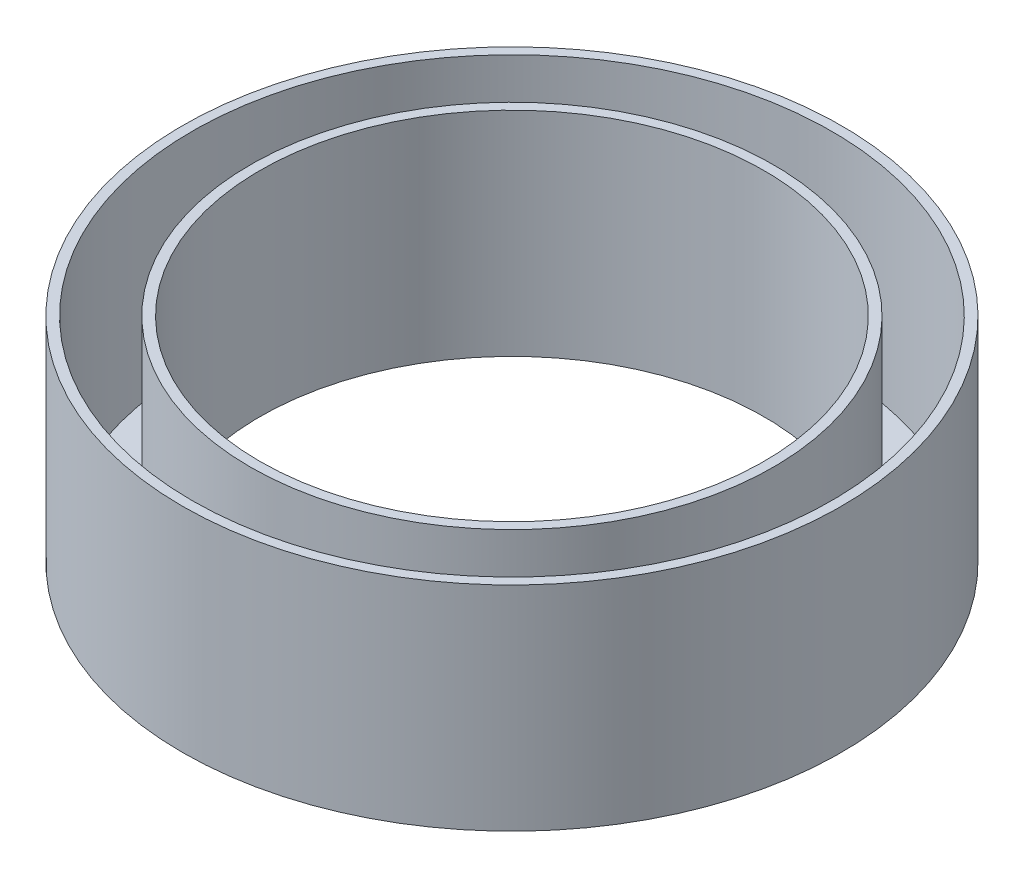
SolidWorks part; units mm, degrees
ref_plane "前视基准面" through (0, 0, 0) normal (0, 0, 1) x (1, 0, 0)
ref_plane "上视基准面" through (0, 0, 0) normal (0, 1, 0) x (1, 0, 0)
ref_plane "右视基准面" through (0, 0, 0) normal (1, 0, 0) x (0, 0, -1)
sketch "草图1" plane through (0, 0, 0) normal (0, 1, 0) x (1, 0, 0)
  circle A0 centre (0, 0) radius 17
  circle A1 centre (0, 0) radius 13
  dimension "D1" = 34
  dimension "D2" = 26
extrude "凸台-拉伸1" add sketch "草图1" along normal blind 11
sketch "草图2" plane through (0, 11, 0) normal (0, 1, 0) x (1, 0, 0)
  circle A0 centre (0, 0) radius 13.5
  circle A1 centre (0, 0) radius 16.5
  circle A2 centre (0, 0) radius 13 construction
  circle A3 centre (0, 0) radius 17 construction
  dimension "D1" = 0.5
  dimension "D2" = 0.5
extrude "切除-拉伸1" cut sketch "草图2" against normal blind 10.6
